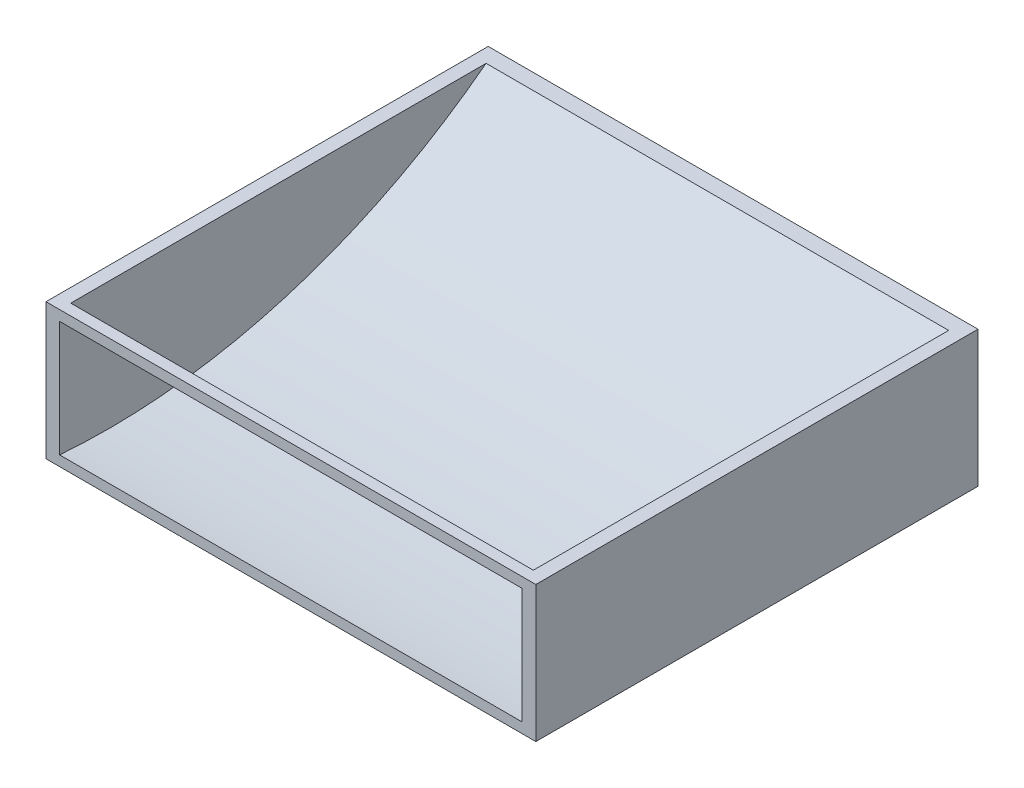
SolidWorks part; units mm, degrees
ref_plane "Front Plane" through (0, 0, 0) normal (0, 0, 1) x (1, 0, 0)
ref_plane "Top Plane" through (0, 0, 0) normal (0, 1, 0) x (1, 0, 0)
ref_plane "Right Plane" through (0, 0, 0) normal (1, 0, 0) x (0, 0, -1)
sketch "Sketch1" plane through (0, 0, 0) normal (0, 0, 1) x (1, 0, 0)
  line L1 (-350, 100) -> (350, 100)
  line L2 (-350, 100) -> (-350, -100)
  line L3 (-350, -100) -> (350, -100)
  line L4 (350, 100) -> (350, -100)
  line L5 (-350, 100) -> (350, -100) construction
  line L6 (-350, -100) -> (350, 100) construction
  point P0 (0, 0)
  dimension "D1" = 700
  dimension "D2" = 200
extrude "Boss-Extrude1" add sketch "Sketch1" against normal blind 650
sketch "Sketch2" plane through (0, 0, 0) normal (0, 0, 1) x (1, 0, 0)
  line L1 (-235, 85) -> (235, 85)
  line L2 (-235, 85) -> (-235, -85)
  line L3 (-235, -85) -> (235, -85)
  line L4 (235, 85) -> (235, -85)
  line L5 (-235, 85) -> (235, -85) construction
  line L6 (-235, -85) -> (235, 85) construction
  point P0 (0, 0)
  dimension "D1" = 470
  dimension "D2" = 170
sketch "Sketch5" plane through (0, 100, 0) normal (0, 1, 0) x (1, 0, 0)
  line L1 (-235, 482.67) -> (235, 482.67)
  line L2 (-235, 482.67) -> (-235, 12.67)
  line L3 (-235, 12.67) -> (235, 12.67)
  line L4 (235, 482.67) -> (235, 12.67)
  line L5 (-235, 482.67) -> (235, 12.67) construction
  line L6 (-235, 12.67) -> (235, 482.67) construction
  point P0 (0, 247.67)
  dimension "D1" = 470
  dimension "D2" = 470
sketch "Sketch6" plane through (350, 0, 0) normal (1, 0, 0) x (0, 0, -1)
  line L0 (482.67, 100) -> (12.67, 100) construction
  line L1 (482.67, 100) -> (12.67, 100) construction
  line L2 (0, -85) -> (0, 85) construction
  line L3 (0, 85) -> (0, -85) construction
  line L4 (12.67, 100) -> (482.67, 100) construction
  line L5 (0, 85) -> (0, -85) construction
  line L6 (650, 100) -> (0, 100) construction
  line L7 (0, 85) -> (0, -85)
  line L8 (16.3469, 100) -> (626.8954, 100)
  arc A0 (626.8954, 100) -> (0, -85) centre (72.3613, 824.4512) cw
  arc A1 (16.3469, 100) -> (0, 85) centre (0.6734, 100.6734) cw
  point P14 (626.8954, 100)
extrude "Cut-Extrude2" cut sketch "Sketch6" against normal blind 680
sketch "Sketch7" plane through (350, 0, 0) normal (1, 0, 0) x (0, 0, -1)
  line L1 (0, 100) -> (650, 100)
  line L2 (0, 100) -> (0, -100)
  line L3 (0, -100) -> (650, -100)
  line L4 (650, 100) -> (650, -100)
extrude "Boss-Extrude3" add sketch "Sketch7" along normal blind 20
ref_plane "middle" through (0, 0, -250) normal (0, 0, 1) x (1, 0, 0)
